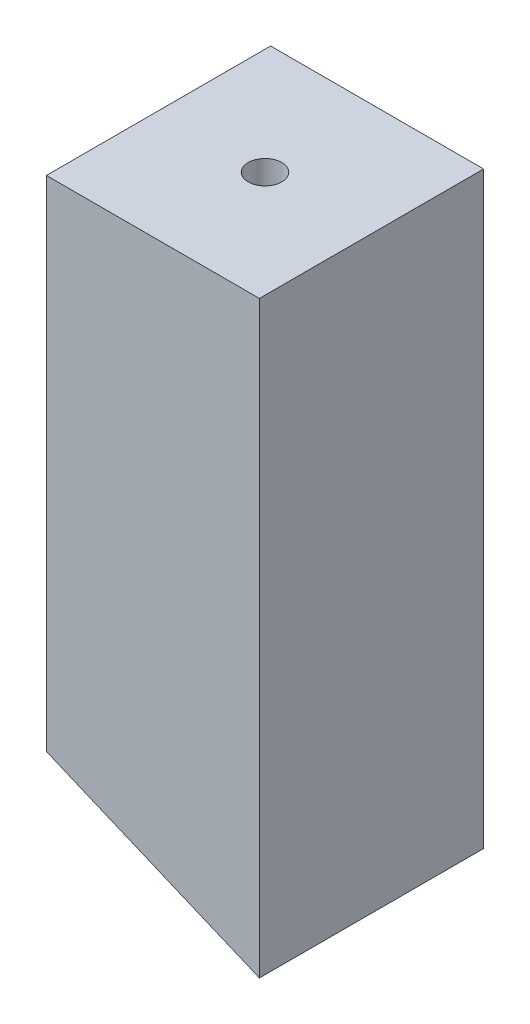
SolidWorks part; units mm, degrees
ref_plane "前视基准面" through (0, 0, 0) normal (0, 0, 1) x (1, 0, 0)
ref_plane "上视基准面" through (0, 0, 0) normal (0, 1, 0) x (1, 0, 0)
ref_plane "右视基准面" through (0, 0, 0) normal (1, 0, 0) x (0, 0, -1)
sketch "草图1" plane through (0, 0, 0) normal (0, 0, 1) x (1, 0, 0)
  line L2 (10.5, 12) -> (29.5, 4)
  line L4 (10.5, 12) -> (10.5, 56.5)
  line L5 (10.5, 56.5) -> (29.5, 56.5)
  line L6 (29.5, 4) -> (29.5, 56.5)
  point P0 (0, 0)
  point P6 (0, 0)
  point P8 (0, 0)
  point P9 (0, 0)
  dimension "D1" = 8
  dimension "D2" = 19
  dimension "D3" = 52.5
extrude "凸台-拉伸1" add sketch "草图1" against normal blind 20
sketch "草图2" plane through (0, 56.5, 0) normal (0, 1, 0) x (1, 0, 0)
  line L0 (29.5, 20) -> (10.5, 20) construction
  line L1 (29.5, 20) -> (29.5, 0) construction
  circle A0 centre (20, 10) radius 1.5
  dimension "D3" = 3
  dimension "D1" = 10
  dimension "D2" = 9.5
extrude "切除-拉伸1" cut sketch "草图2" against normal blind 20
